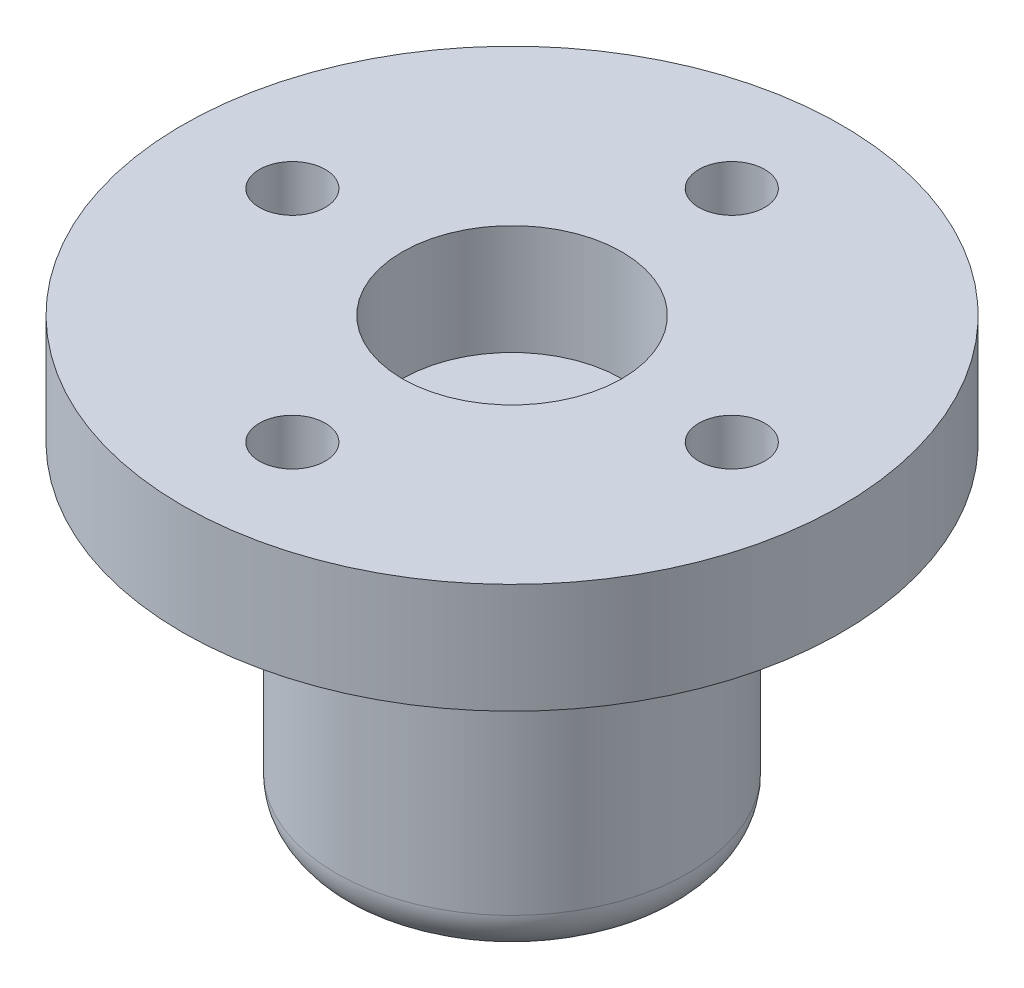
SolidWorks part; units mm, degrees
ref_plane "Front Plane" through (0, 0, 0) normal (0, 0, 1) x (1, 0, 0)
ref_plane "Top Plane" through (0, 0, 0) normal (0, 1, 0) x (1, 0, 0)
ref_plane "Right Plane" through (0, 0, 0) normal (1, 0, 0) x (0, 0, -1)
sketch "Sketch2" plane through (0, 0, 0) normal (0, 1, 0) x (1, 0, 0)
  circle A0 centre (0, 0) radius 19.05
  circle A1 centre (0, 0) radius 6.35
  circle A2 centre (0, 0) radius 12.7 construction
  circle A3 centre (0, 12.7) radius 1.905
  circle A4 centre (12.7, 0) radius 1.905
  circle A5 centre (0, -12.7) radius 1.905
  circle A6 centre (-12.7, 0) radius 1.905
  point P16 (0, 0)
  dimension "D1" = 38.1
  dimension "D2" = 12.7
  dimension "D3" = 25.4
  dimension "D4" = 3.81
  dimension "D5" = 4
extrude "Boss-Extrude1" add sketch "Sketch2" against normal blind 6.35
sketch "Sketch3" plane through (0, -6.35, 0) normal (0, -1, 0) x (1, 0, 0)
  circle A0 centre (0, 0) radius 10.16
  dimension "D1" = 20.32
extrude "Boss-Extrude2" add sketch "Sketch3" along normal blind 19.05
fillet "Fillet1" radius 2.54 1 edges at (0, -25.4, -10.16)
sketch "Sketch5" plane through (0, -25.4, 0) normal (0, -1, 0) x (1, 0, 0)
  line L0 (0, -11.766) -> (0, 11.6045) construction
  line L1 (0, 7.62) -> (0, -7.62)
  arc A0 (0, -7.62) -> (0, 7.62) centre (0, 0) ccw
revolve "Revolve1" add sketch "Sketch5" angle 360 about L0
combine bodies "Combine1" operation type subtract main body 102 bodies to subtract 103
